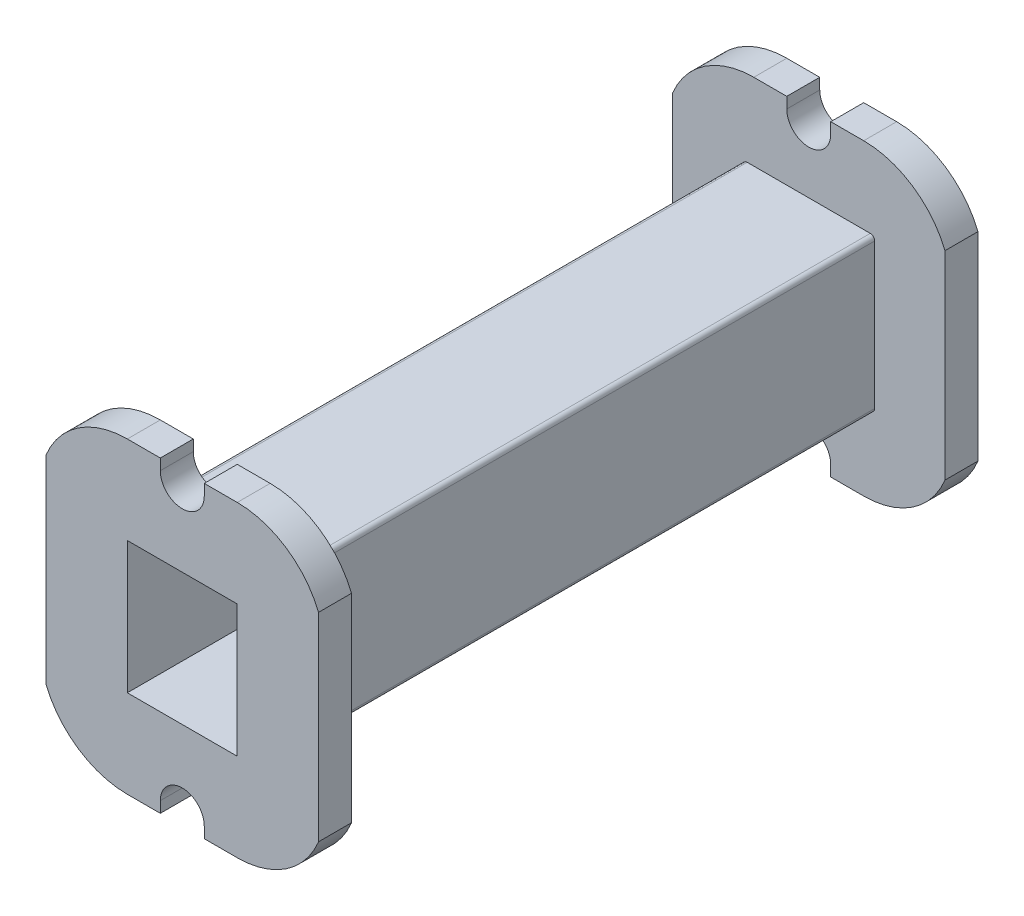
SolidWorks part; units mm, degrees
ref_plane "前视基准面" through (0, 0, 0) normal (0, 0, 1) x (1, 0, 0)
ref_plane "上视基准面" through (0, 0, 0) normal (0, 1, 0) x (1, 0, 0)
ref_plane "右视基准面" through (0, 0, 0) normal (1, 0, 0) x (0, 0, -1)
sketch "草图1" plane through (0, 0, 0) normal (0, 0, 1) x (1, 0, 0)
  line L0 (-3, 3.5) -> (3, 3.5)
  line L1 (-2.5, 3) -> (2.5, 3)
  line L2 (-2.5, 3) -> (-2.5, -3)
  line L3 (-2.5, -3) -> (2.5, -3)
  line L4 (2.5, 3) -> (2.5, -3)
  line L5 (-2.5, 3) -> (2.5, -3) construction
  line L6 (-2.5, -3) -> (2.5, 3) construction
  line L7 (3, 3.5) -> (3, -3.5)
  line L8 (-3, -3.5) -> (3, -3.5)
  line L9 (-3, 3.5) -> (-3, -3.5)
  point P0 (0, 0)
  dimension "D1" = 5
  dimension "D2" = 6
  dimension "D3" = 0.5
extrude "凸台-拉伸1" add sketch "草图1" along normal mid plane 30
sketch "草图2" plane through (0, 0, 15) normal (0, 0, 1) x (1, 0, 0)
  line L1 (-3, -3.5) -> (3, -3.5)
  line L2 (-3, -3.5) -> (-3, 3.5)
  line L3 (-3, 3.5) -> (3, 3.5)
  line L4 (3, -3.5) -> (3, 3.5)
  line L5 (-3, -3.5) -> (3, 3.5) construction
  line L6 (-3, 3.5) -> (3, -3.5) construction
  line L7 (-6.5, -10.75) -> (6.5, -10.75)
  line L8 (-6.5, -10.75) -> (-6.5, 10.75)
  line L9 (-6.5, 10.75) -> (6.5, 10.75)
  line L10 (6.5, -10.75) -> (6.5, 10.75)
  line L11 (-6.5, -10.75) -> (6.5, 10.75) construction
  line L12 (-6.5, 10.75) -> (6.5, -10.75) construction
  circle A0 centre (0, 0) radius 9.5
  point P0 (0, 0)
  point P7 (0, 0)
  line M3 (-3, 3.5) -> (-3, -3.5)
  line M4 (-3, -3.5) -> (3, -3.5)
  line M5 (3, -3.5) -> (3, 3.5)
  line M6 (3, 3.5) -> (-3, 3.5)
  dimension "D3" = 19
  dimension "D1" = 13
  dimension "D2" = 21.5
extrude "凸台-拉伸2" add sketch "草图2" against normal blind 1.5 contours L10 A0 L8 M3 M6 M5 M4
mirror "镜向1" about plane through (0, 0, 0) normal (0, 0, 1) of "凸台-拉伸2"
sketch "草图3" plane through (0, 0, 15) normal (0, 0, 1) x (1, 0, 0)
  line L1 (-9.3579, 7) -> (9.3579, 7)
  line L2 (-9.3579, 7) -> (-9.3579, -7)
  line L3 (-9.3579, -7) -> (9.3579, -7)
  line L4 (9.3579, 7) -> (9.3579, -7)
  line L5 (-9.3579, 7) -> (9.3579, -7) construction
  line L6 (-9.3579, -7) -> (9.3579, 7) construction
  circle A0 centre (0, 0) radius 19.1004
  point P0 (0, 0)
  dimension "D1" = 14
extrude "切除-拉伸1" cut sketch "草图3" against normal through all
sketch "草图4" plane through (0, 0, 15) normal (0, 0, 1) x (1, 0, 0)
  line L4 (-6.4226, -7) -> (6.4226, -7)
  line L5 (6.5, -6.9282) -> (6.5, 6.9282)
  line L6 (6.4226, 7) -> (-6.4226, 7)
  line L7 (-6.5, 6.9282) -> (-6.5, -6.9282)
  line L8 (-6.4226, -7) -> (6.4226, -7)
  line L9 (6.5, -6.9282) -> (6.5, 6.9282)
  line L10 (6.4226, 7) -> (-6.4226, 7)
  line L11 (-6.5, 6.9282) -> (-6.5, -6.9282)
  circle A0 centre (-2.5, 3) radius 4
  circle A1 centre (2.5, 3) radius 4
  circle A2 centre (2.5, -3) radius 4
  circle A3 centre (-2.5, -3) radius 4
  arc A8 (-6.5, -6.9282) -> (-6.4226, -7) centre (0, 0) ccw
  arc A9 (6.4226, -7) -> (6.5, -6.9282) centre (0, 0) ccw
  arc A10 (6.5, 6.9282) -> (6.4226, 7) centre (0, 0) ccw
  arc A11 (-6.4226, 7) -> (-6.5, 6.9282) centre (0, 0) ccw
  arc A12 (-6.5, -6.9282) -> (-6.4226, -7) centre (0, 0) ccw
  arc A13 (6.4226, -7) -> (6.5, -6.9282) centre (0, 0) ccw
  arc A14 (6.5, 6.9282) -> (6.4226, 7) centre (0, 0) ccw
  arc A15 (-6.4226, 7) -> (-6.5, 6.9282) centre (0, 0) ccw
  arc M17 (-6.5, -6.9282) -> (-6.4226, -7) centre (0, 0) ccw
  line M18 (-6.4226, -7) -> (6.4226, -7)
  arc M19 (6.4226, -7) -> (6.5, -6.9282) centre (0, 0) ccw
  line M20 (6.5, -6.9282) -> (6.5, 6.9282)
  arc M21 (6.5, 6.9282) -> (6.4226, 7) centre (0, 0) ccw
  line M22 (6.4226, 7) -> (-6.4226, 7)
  arc M23 (-6.4226, 7) -> (-6.5, 6.9282) centre (0, 0) ccw
  line M24 (-6.5, 6.9282) -> (-6.5, -6.9282)
  dimension "D1" = 0
extrude "切除-拉伸2" cut sketch "草图4" against normal through all contours A0 L10 M23 M24 | A1 L9 M21 M22 | A2 L8 M19 M20 | A3 M24 M17 M18
sketch "草图5" plane through (0, 0, 15) normal (0, 0, 1) x (1, 0, 0)
  line L0 (0, 7.5) -> (0, 6.5) construction
  line L1 (-6.2, 12.6435) -> (6.2, 12.6435)
  line L2 (-6.2, 12.6435) -> (-6.2, -12.6435)
  line L3 (-6.2, -12.6435) -> (6.2, -12.6435)
  line L4 (6.2, 12.6435) -> (6.2, -12.6435)
  line L5 (-6.2, 12.6435) -> (6.2, -12.6435) construction
  line L6 (-6.2, -12.6435) -> (6.2, 12.6435) construction
  line L7 (2.5, 7) -> (-2.5, 7) construction
  line L8 (1, 7.5) -> (1, 6.5)
  line L9 (-1, 7.5) -> (-1, 6.5)
  line L10 (0, -6.5) -> (0, -7.5) construction
  line L11 (-2.5, -7) -> (2.5, -7) construction
  line L12 (1, -6.5) -> (1, -7.5)
  line L13 (-1, -6.5) -> (-1, -7.5)
  line L14 (6.5, -3) -> (6.5, 3) construction
  line L16 (-13.2201, 15.7714) -> (13.2201, 15.7714)
  line L17 (-13.2201, 15.7714) -> (-13.2201, -15.7714)
  line L18 (-13.2201, -15.7714) -> (13.2201, -15.7714)
  line L19 (13.2201, 15.7714) -> (13.2201, -15.7714)
  line L20 (-13.2201, 15.7714) -> (13.2201, -15.7714) construction
  line L21 (-13.2201, -15.7714) -> (13.2201, 15.7714) construction
  arc A0 (1, 7.5) -> (-1, 7.5) centre (0, 7.5) ccw
  arc A1 (-1, 6.5) -> (1, 6.5) centre (0, 6.5) ccw
  arc A2 (1, -6.5) -> (-1, -6.5) centre (0, -6.5) ccw
  arc A3 (-1, -7.5) -> (1, -7.5) centre (0, -7.5) ccw
  point P0 (0, 0)
  point P10 (0, 7)
  point P16 (0, -7)
  point P26 (0, 0)
  line M11 (-6.5, 3) -> (-6.5, -3)
  arc M12 (-6.5, -3) -> (-2.5, -7) centre (-2.5, -3) ccw
  line M13 (-2.5, -7) -> (2.5, -7)
  arc M14 (2.5, -7) -> (6.5, -3) centre (2.5, -3) ccw
  line M15 (6.5, -3) -> (6.5, 3)
  arc M16 (6.5, 3) -> (2.5, 7) centre (2.5, 3) ccw
  line M17 (2.5, 7) -> (-2.5, 7)
  arc M18 (-2.5, 7) -> (-6.5, 3) centre (-2.5, 3) ccw
  dimension "D1" = 1
  dimension "D2" = 1
  dimension "D3" = 1
  dimension "D4" = 1
  dimension "D5" = 0.3
extrude "切除-拉伸3" cut sketch "草图5" against normal through all both and the other way through all contours L9 A1 L8 M17 | L12 A2 L13 M13 | L2 M18 M11 M12 | L4 M16 M14 M15
fillet "圆角1" radius 0.2 4 edges at (3, 3.5, 0) (-3, -3.5, 0) (-3, 3.5, 0) (3, -3.5, 0)
